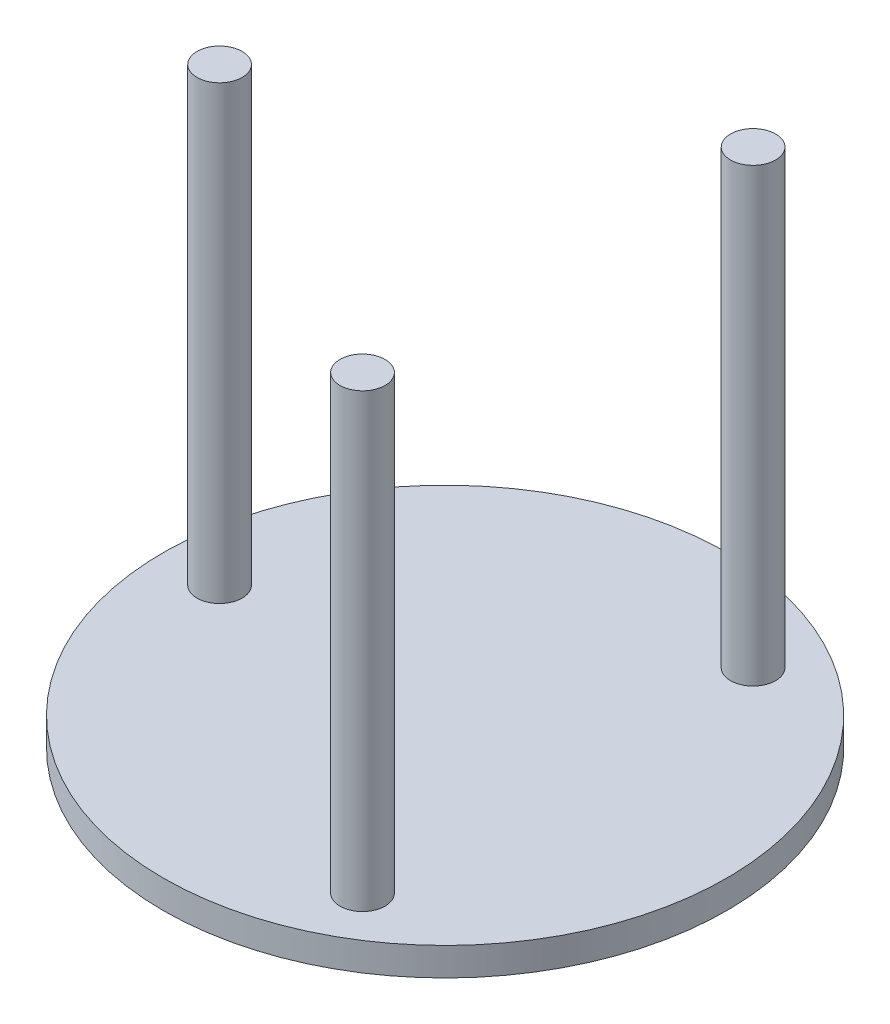
SolidWorks part; units mm, degrees
ref_plane "Front Plane" through (0, 0, 0) normal (0, 0, 1) x (1, 0, 0)
ref_plane "Top Plane" through (0, 0, 0) normal (0, 1, 0) x (1, 0, 0)
ref_plane "Right Plane" through (0, 0, 0) normal (1, 0, 0) x (0, 0, -1)
sketch "Sketch1" plane through (0, 0, 0) normal (0, 1, 0) x (1, 0, 0)
  circle A0 centre (0, 0) radius 50
  dimension "D1" = 100
extrude "Boss-Extrude1" add sketch "Sketch1" along normal blind 5
sketch "Sketch2" plane through (0, 5, 0) normal (0, 1, 0) x (1, 0, 0)
  line L0 (0, 50) -> (0, -50) construction
  line L1 (-50, 0) -> (50, 0) construction
  circle A0 centre (0, 0) radius 50 construction
  circle A1 centre (0, 0) radius 40 construction
  circle A2 centre (-40, 0) radius 4
  circle A3 centre (20, 34.641) radius 4
  circle A4 centre (20, -34.641) radius 4
  point P20 (0, 0)
  dimension "D1" = 80
  dimension "D2" = 8
  dimension "D3" = 3
extrude "Boss-Extrude2" add sketch "Sketch2" along normal blind 80
